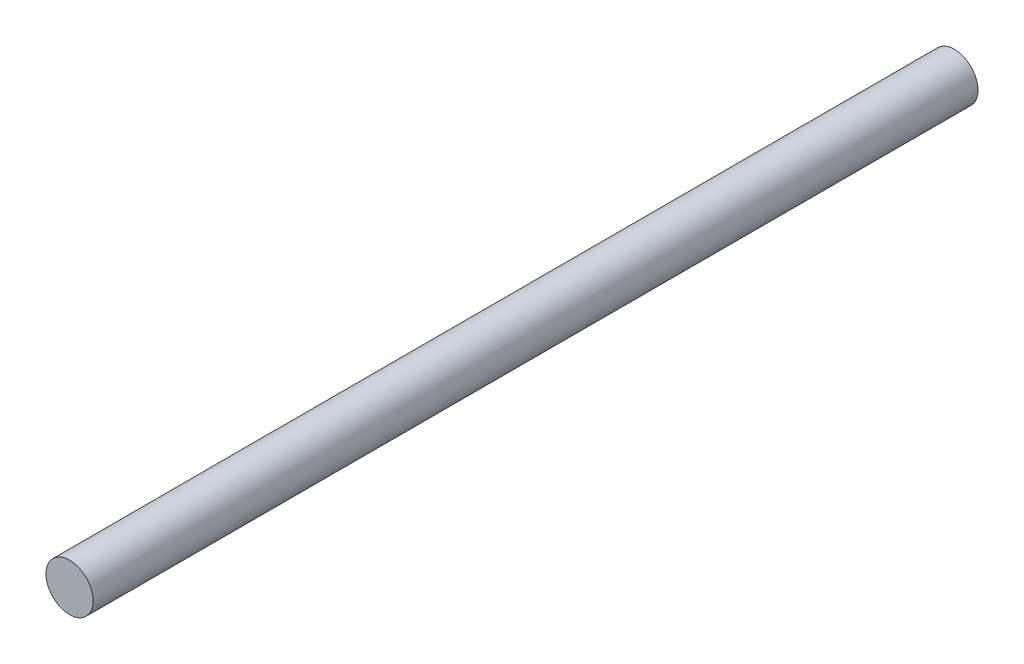
SolidWorks part; units mm, degrees
ref_plane "前视基准面" through (0, 0, 0) normal (0, 0, 1) x (1, 0, 0)
ref_plane "上视基准面" through (0, 0, 0) normal (0, 1, 0) x (1, 0, 0)
ref_plane "右视基准面" through (0, 0, 0) normal (1, 0, 0) x (0, 0, -1)
sketch "草图1" plane through (0, 0, 0) normal (0, 0, 1) x (1, 0, 0)
  circle A0 centre (0, 0) radius 8
  dimension "D1" = 16
extrude "凸台-拉伸1" add sketch "草图1" along normal blind 300
